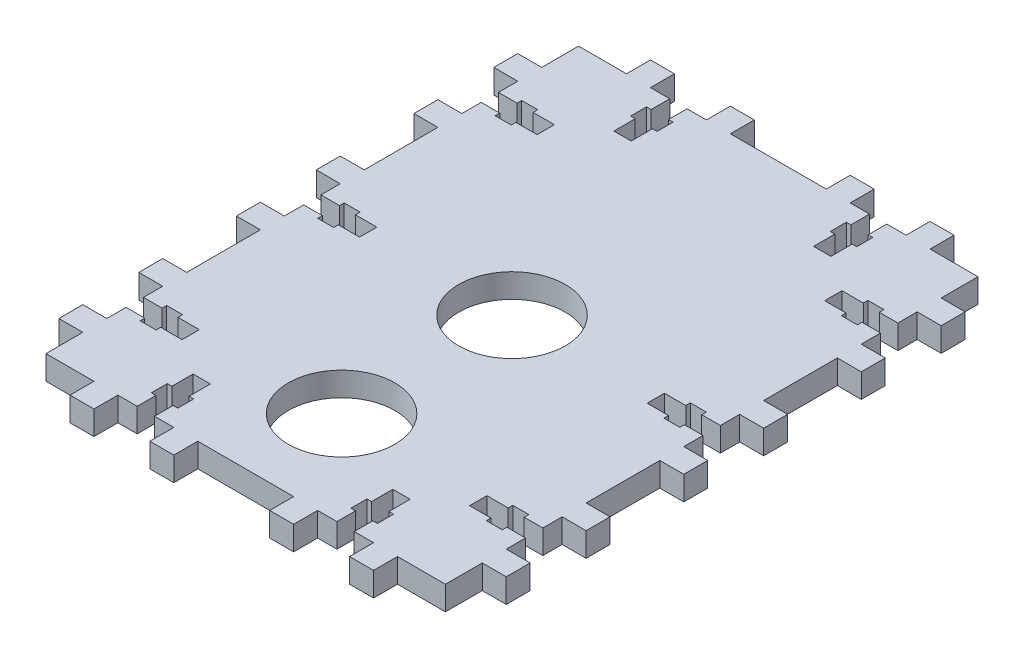
SolidWorks part; units mm, degrees
ref_plane "Front Plane" through (0, 0, 0) normal (0, 0, 1) x (1, 0, 0)
ref_plane "Top Plane" through (0, 0, 0) normal (0, 1, 0) x (1, 0, 0)
ref_plane "Right Plane" through (0, 0, 0) normal (1, 0, 0) x (0, 0, -1)
sketch "Sketch1" plane through (0, 0, 0) normal (0, 1, 0) x (1, 0, 0)
  line L0 (0, 0) -> (0, -100) construction
  line L1 (-75, -100) -> (75, -100)
  line L2 (-75, -100) -> (-75, 100)
  line L3 (-75, 100) -> (75, 100)
  line L4 (75, -100) -> (75, 100)
  line L5 (-75, -100) -> (75, 100) construction
  line L6 (-75, 100) -> (75, -100) construction
  line L7 (0, 0) -> (75, 0) construction
  line L8 (75, -32) -> (-75, -32) construction
  line L9 (-110, 72.5) -> (110, 72.5) construction
  circle A0 centre (0, 0) radius 20
  circle A6 centre (0, -64) radius 20
  point P0 (0, 0)
  point P8 (0, 0)
  point P9 (0, 0)
  point P12 (0, 0)
  point P17 (0, 0)
  point P18 (0, 0)
  point P19 (0, 0)
  point P20 (0, 0)
  point P28 (1.8733, 2.7633)
  line B0 (-57, -100) -> (-57, -109)
  line B1 (-57, -109) -> (-48, -109)
  line B2 (-48, -109) -> (-48, -100)
  line B3 (-48, -100) -> (-40.75, -100)
  line B4 (-40.75, -100) -> (-40.75, -93)
  line B5 (-40.75, -93) -> (-42.475, -93)
  line B6 (-42.475, -93) -> (-42.475, -87)
  line B7 (-42.475, -87) -> (-40.75, -87)
  line B8 (-40.75, -87) -> (-40.75, -79)
  line B9 (-40.75, -79) -> (-34.25, -79)
  line B10 (-37.5, -79) -> (-37.5, -100) construction
  line B11 (-34.25, -87) -> (-34.25, -79)
  line B12 (-32.525, -87) -> (-34.25, -87)
  line B13 (-32.525, -93) -> (-32.525, -87)
  line B14 (-34.25, -93) -> (-32.525, -93)
  line B15 (-34.25, -100) -> (-34.25, -93)
  line B16 (-27, -100) -> (-34.25, -100)
  line B17 (-27, -109) -> (-27, -100)
  line B18 (-18, -109) -> (-27, -109)
  line B19 (-18, -100) -> (-18, -109)
  line B20 (18, -100) -> (18, -109)
  line B21 (18, -109) -> (27, -109)
  line B22 (27, -109) -> (27, -100)
  line B23 (27, -100) -> (34.25, -100)
  line B24 (34.25, -100) -> (34.25, -93)
  line B25 (34.25, -93) -> (32.525, -93)
  line B26 (32.525, -93) -> (32.525, -87)
  line B27 (32.525, -87) -> (34.25, -87)
  line B28 (34.25, -87) -> (34.25, -79)
  line B29 (34.25, -79) -> (40.75, -79)
  line B30 (37.5, -79) -> (37.5, -100) construction
  line B31 (40.75, -87) -> (40.75, -79)
  line B32 (42.475, -87) -> (40.75, -87)
  line B33 (42.475, -93) -> (42.475, -87)
  line B34 (40.75, -93) -> (42.475, -93)
  line B35 (40.75, -100) -> (40.75, -93)
  line B36 (48, -100) -> (40.75, -100)
  line B37 (48, -109) -> (48, -100)
  line B38 (57, -109) -> (48, -109)
  line B39 (57, -100) -> (57, -109)
  line B40 (75, -19.5) -> (84, -19.5)
  line B41 (84, -19.5) -> (84, -10.5)
  line B42 (84, -10.5) -> (75, -10.5)
  line B43 (75, -10.5) -> (75, -3.25)
  line B44 (75, -3.25) -> (68, -3.25)
  line B45 (68, -3.25) -> (68, -4.975)
  line B46 (68, -4.975) -> (62, -4.975)
  line B47 (62, -4.975) -> (62, -3.25)
  line B48 (62, -3.25) -> (54, -3.25)
  line B49 (54, -3.25) -> (54, 3.25)
  line B50 (54, 0) -> (75, 0) construction
  line B51 (62, 3.25) -> (54, 3.25)
  line B52 (62, 4.975) -> (62, 3.25)
  line B53 (68, 4.975) -> (62, 4.975)
  line B54 (68, 3.25) -> (68, 4.975)
  line B55 (75, 3.25) -> (68, 3.25)
  line B56 (75, 10.5) -> (75, 3.25)
  line B57 (84, 10.5) -> (75, 10.5)
  line B58 (84, 19.5) -> (84, 10.5)
  line B59 (75, 19.5) -> (84, 19.5)
  line B60 (75, 47.1667) -> (84, 47.1667)
  line B61 (84, 47.1667) -> (84, 56.1667)
  line B62 (84, 56.1667) -> (75, 56.1667)
  line B63 (75, 56.1667) -> (75, 63.4167)
  line B64 (75, 63.4167) -> (68, 63.4167)
  line B65 (68, 63.4167) -> (68, 61.6917)
  line B66 (68, 61.6917) -> (62, 61.6917)
  line B67 (62, 61.6917) -> (62, 63.4167)
  line B68 (62, 63.4167) -> (54, 63.4167)
  line B69 (54, 63.4167) -> (54, 69.9167)
  line B70 (54, 66.6667) -> (75, 66.6667) construction
  line B71 (62, 69.9167) -> (54, 69.9167)
  line B72 (62, 71.6417) -> (62, 69.9167)
  line B73 (68, 71.6417) -> (62, 71.6417)
  line B74 (68, 69.9167) -> (68, 71.6417)
  line B75 (75, 69.9167) -> (68, 69.9167)
  line B76 (75, 77.1667) -> (75, 69.9167)
  line B77 (84, 77.1667) -> (75, 77.1667)
  line B78 (84, 86.1667) -> (84, 77.1667)
  line B79 (75, 86.1667) -> (84, 86.1667)
  line B80 (75, -86.1667) -> (84, -86.1667)
  line B81 (84, -86.1667) -> (84, -77.1667)
  line B82 (84, -77.1667) -> (75, -77.1667)
  line B83 (75, -77.1667) -> (75, -69.9167)
  line B84 (75, -69.9167) -> (68, -69.9167)
  line B85 (68, -69.9167) -> (68, -71.6417)
  line B86 (68, -71.6417) -> (62, -71.6417)
  line B87 (62, -71.6417) -> (62, -69.9167)
  line B88 (62, -69.9167) -> (54, -69.9167)
  line B89 (54, -69.9167) -> (54, -63.4167)
  line B90 (54, -66.6667) -> (75, -66.6667) construction
  line B91 (62, -63.4167) -> (54, -63.4167)
  line B92 (62, -61.6917) -> (62, -63.4167)
  line B93 (68, -61.6917) -> (62, -61.6917)
  line B94 (68, -63.4167) -> (68, -61.6917)
  line B95 (75, -63.4167) -> (68, -63.4167)
  line B96 (75, -56.1667) -> (75, -63.4167)
  line B97 (84, -56.1667) -> (75, -56.1667)
  line B98 (84, -47.1667) -> (84, -56.1667)
  line B99 (75, -47.1667) -> (84, -47.1667)
  line B100 (-75, -19.5) -> (-84, -19.5)
  line B101 (-84, -19.5) -> (-84, -10.5)
  line B102 (-84, -10.5) -> (-75, -10.5)
  line B103 (-75, -10.5) -> (-75, -3.25)
  line B104 (-75, -3.25) -> (-68, -3.25)
  line B105 (-68, -3.25) -> (-68, -4.975)
  line B106 (-68, -4.975) -> (-62, -4.975)
  line B107 (-62, -4.975) -> (-62, -3.25)
  line B108 (-62, -3.25) -> (-54, -3.25)
  line B109 (-54, -3.25) -> (-54, 3.25)
  line B110 (-54, 0) -> (-75, 0) construction
  line B111 (-62, 3.25) -> (-54, 3.25)
  line B112 (-62, 4.975) -> (-62, 3.25)
  line B113 (-68, 4.975) -> (-62, 4.975)
  line B114 (-68, 3.25) -> (-68, 4.975)
  line B115 (-75, 3.25) -> (-68, 3.25)
  line B116 (-75, 10.5) -> (-75, 3.25)
  line B117 (-84, 10.5) -> (-75, 10.5)
  line B118 (-84, 19.5) -> (-84, 10.5)
  line B119 (-75, 19.5) -> (-84, 19.5)
  line B120 (-75, 47.1667) -> (-84, 47.1667)
  line B121 (-84, 47.1667) -> (-84, 56.1667)
  line B122 (-84, 56.1667) -> (-75, 56.1667)
  line B123 (-75, 56.1667) -> (-75, 63.4167)
  line B124 (-75, 63.4167) -> (-68, 63.4167)
  line B125 (-68, 63.4167) -> (-68, 61.6917)
  line B126 (-68, 61.6917) -> (-62, 61.6917)
  line B127 (-62, 61.6917) -> (-62, 63.4167)
  line B128 (-62, 63.4167) -> (-54, 63.4167)
  line B129 (-54, 63.4167) -> (-54, 69.9167)
  line B130 (-54, 66.6667) -> (-75, 66.6667) construction
  line B131 (-62, 69.9167) -> (-54, 69.9167)
  line B132 (-62, 71.6417) -> (-62, 69.9167)
  line B133 (-68, 71.6417) -> (-62, 71.6417)
  line B134 (-68, 69.9167) -> (-68, 71.6417)
  line B135 (-75, 69.9167) -> (-68, 69.9167)
  line B136 (-75, 77.1667) -> (-75, 69.9167)
  line B137 (-84, 77.1667) -> (-75, 77.1667)
  line B138 (-84, 86.1667) -> (-84, 77.1667)
  line B139 (-75, 86.1667) -> (-84, 86.1667)
  line B140 (-75, -86.1667) -> (-84, -86.1667)
  line B141 (-84, -86.1667) -> (-84, -77.1667)
  line B142 (-84, -77.1667) -> (-75, -77.1667)
  line B143 (-75, -77.1667) -> (-75, -69.9167)
  line B144 (-75, -69.9167) -> (-68, -69.9167)
  line B145 (-68, -69.9167) -> (-68, -71.6417)
  line B146 (-68, -71.6417) -> (-62, -71.6417)
  line B147 (-62, -71.6417) -> (-62, -69.9167)
  line B148 (-62, -69.9167) -> (-54, -69.9167)
  line B149 (-54, -69.9167) -> (-54, -63.4167)
  line B150 (-54, -66.6667) -> (-75, -66.6667) construction
  line B151 (-62, -63.4167) -> (-54, -63.4167)
  line B152 (-62, -61.6917) -> (-62, -63.4167)
  line B153 (-68, -61.6917) -> (-62, -61.6917)
  line B154 (-68, -63.4167) -> (-68, -61.6917)
  line B155 (-75, -63.4167) -> (-68, -63.4167)
  line B156 (-75, -56.1667) -> (-75, -63.4167)
  line B157 (-84, -56.1667) -> (-75, -56.1667)
  line B158 (-84, -47.1667) -> (-84, -56.1667)
  line B159 (-75, -47.1667) -> (-84, -47.1667)
  line B160 (-57, 100) -> (-57, 109)
  line B161 (-57, 109) -> (-48, 109)
  line B162 (-48, 109) -> (-48, 100)
  line B163 (-48, 100) -> (-40.75, 100)
  line B164 (-40.75, 100) -> (-40.75, 93)
  line B165 (-40.75, 93) -> (-42.475, 93)
  line B166 (-42.475, 93) -> (-42.475, 87)
  line B167 (-42.475, 87) -> (-40.75, 87)
  line B168 (-40.75, 87) -> (-40.75, 79)
  line B169 (-40.75, 79) -> (-34.25, 79)
  line B170 (-37.5, 79) -> (-37.5, 100) construction
  line B171 (-34.25, 87) -> (-34.25, 79)
  line B172 (-32.525, 87) -> (-34.25, 87)
  line B173 (-32.525, 93) -> (-32.525, 87)
  line B174 (-34.25, 93) -> (-32.525, 93)
  line B175 (-34.25, 100) -> (-34.25, 93)
  line B176 (-27, 100) -> (-34.25, 100)
  line B177 (-27, 109) -> (-27, 100)
  line B178 (-18, 109) -> (-27, 109)
  line B179 (-18, 100) -> (-18, 109)
  line B180 (18, 100) -> (18, 109)
  line B181 (18, 109) -> (27, 109)
  line B182 (27, 109) -> (27, 100)
  line B183 (27, 100) -> (34.25, 100)
  line B184 (34.25, 100) -> (34.25, 93)
  line B185 (34.25, 93) -> (32.525, 93)
  line B186 (32.525, 93) -> (32.525, 87)
  line B187 (32.525, 87) -> (34.25, 87)
  line B188 (34.25, 87) -> (34.25, 79)
  line B189 (34.25, 79) -> (40.75, 79)
  line B190 (37.5, 79) -> (37.5, 100) construction
  line B191 (40.75, 87) -> (40.75, 79)
  line B192 (42.475, 87) -> (40.75, 87)
  line B193 (42.475, 93) -> (42.475, 87)
  line B194 (40.75, 93) -> (42.475, 93)
  line B195 (40.75, 100) -> (40.75, 93)
  line B196 (48, 100) -> (40.75, 100)
  line B197 (48, 109) -> (48, 100)
  line B198 (57, 109) -> (48, 109)
  line B199 (57, 100) -> (57, 109)
  dimension "D7" = 40
  dimension "D1" = 150
  dimension "D2" = 200
  dimension "D3" = 37.5
  dimension "D4" = 33.3333
  dimension "D5" = 64
  dimension "D10" = 32
sketch_block_instance "Plot_9mm_M6_bois-1"
sketch_block "Plot_9mm_M6_bois" parameters "D1"=9, "D2"=9, "D3"=16, "D4"=30, "D5"=9.95, "D6"=6.5, "D7"=6, "D8"=8
sketch_block_instance "Plot_9mm_M6_bois-3"
sketch_block_instance "Plot_9mm_M6_bois-12"
sketch_block_instance "Plot_9mm_M6_bois-14"
sketch_block_instance "Plot_9mm_M6_bois-21"
sketch_block_instance "Plot_9mm_M6_bois-22"
sketch_block_instance "Plot_9mm_M6_bois-23"
sketch_block_instance "Plot_9mm_M6_bois-24"
sketch_block_instance "Plot_9mm_M6_bois-25"
sketch_block_instance "Plot_9mm_M6_bois-26"
sketch_block_instance "Plot_9mm_M6_bois-27"
extrude "Boss-Extrude1" add sketch "Sketch1" along normal blind 9
sketch "Sketch3" plane through (0, 9, 0) normal (0, 1, 0) x (1, 0, 0)
  line L0 (-75, 37.1117) -> (75, 37.1117) construction
  line L1 (75, 19.5) -> (75, 47.1667) construction
  line L2 (-75, 19.5) -> (-75, 47.1667) construction
  text T0 "<b>Mini Tog'</b>\r\n" font "Century Gothic" height 20
  point P2 (0, 0)
  point P5 (0, 0)
